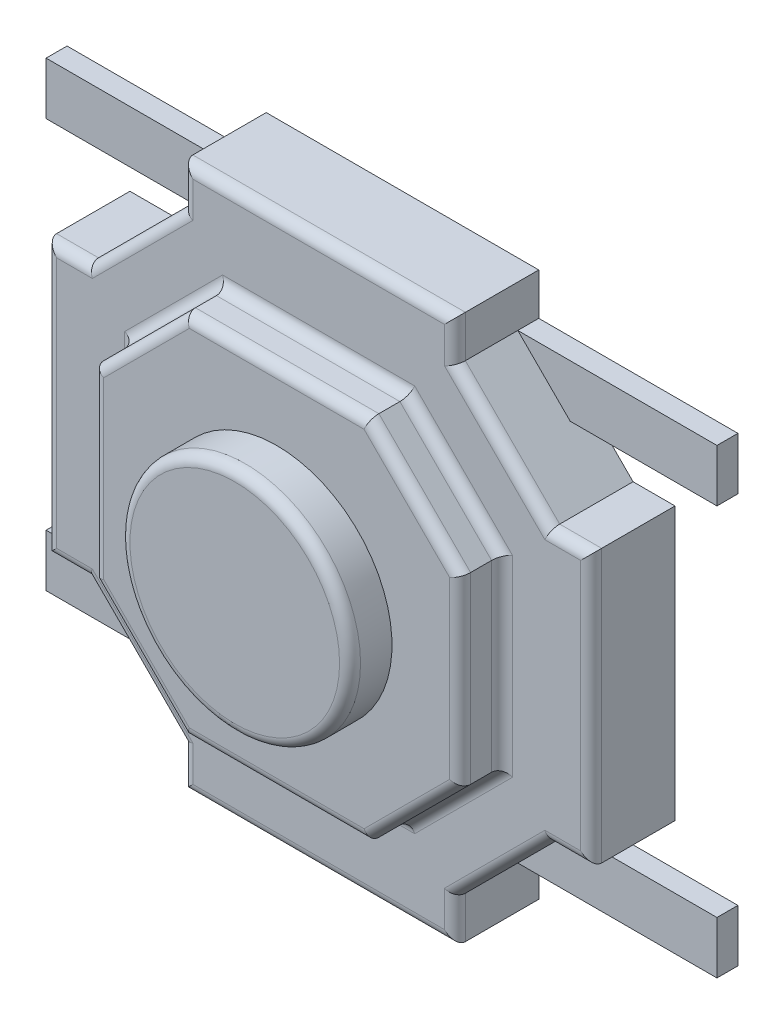
SolidWorks part; units mm, degrees
ref_plane "Plan de face" through (0, 0, 0) normal (0, 0, 1) x (1, 0, 0)
ref_plane "Plan de dessus" through (0, 0, 0) normal (0, 1, 0) x (1, 0, 0)
ref_plane "Plan de droite" through (0, 0, 0) normal (1, 0, 0) x (0, 0, -1)
sketch "Sketch1" plane through (0, 0, 0) normal (0, 0, 1) x (1, 0, 0)
  line L0 (0, 2.6) -> (0, -2.6) construction
  line L1 (-1.3, 2.6) -> (1.3, 2.6)
  line L2 (-2.6, 1.3) -> (-2.6, -1.3)
  line L3 (-1.3, -2.6) -> (1.3, -2.6)
  line L4 (2.6, 1.3) -> (2.6, -1.3)
  line L5 (-2.6, 2.6) -> (2.6, -2.6) construction
  line L6 (-3.9775, -1.9888) -> (2.6, 1.3) construction
  line L7 (-2.6, 0) -> (2.6, 0) construction
  line L8 (-1.3, 2.6) -> (-1.3, -2.6) construction
  line L9 (1.3, 2.6) -> (1.3, -2.6) construction
  line L10 (-2.6, 1.3) -> (2.6, 1.3) construction
  line L11 (-2.6, -1.3) -> (2.6, -1.3) construction
  line L12 (-1.3, -2.6) -> (-1.3, -2.2)
  line L13 (-1.3, -2.2) -> (-2.2, -1.3)
  line L14 (-2.2, -1.3) -> (-2.6, -1.3)
  line L15 (1.3, -2.6) -> (1.3, -2.2)
  line L16 (1.3, -2.2) -> (2.2, -1.3)
  line L17 (2.2, -1.3) -> (2.6, -1.3)
  line L18 (-1.3, 2.2) -> (-2.2, 1.3)
  line L19 (-1.3, 2.6) -> (-1.3, 2.2)
  line L20 (2.2, 1.3) -> (2.6, 1.3)
  line L21 (1.3, 2.6) -> (1.3, 2.2)
  line L22 (1.3, 2.2) -> (2.2, 1.3)
  line L23 (-2.6, 1.3) -> (-2.2, 1.3)
  line L24 (-1.75, 1.75) -> (1.75, 1.75) construction
  line L25 (1.75, 1.75) -> (-1.75, -1.75) construction
  line L26 (-1.75, -1.75) -> (1.75, -1.75) construction
  point P0 (0, 0)
  dimension "D3" = 1.3
  dimension "D6" = 1.3
  dimension "D7" = 0.4
  dimension "D8" = 0.4
extrude "Boss-Extrude1" add sketch "Sketch1" along normal blind 0.8
sketch "Sketch3" plane through (0, 0, 0) normal (0, 0, 1) x (1, 0, 0)
  line L4 (1.3, -2.2) -> (2.2, -1.3) construction
  line L5 (1.75, -1.75) -> (-1.75, -1.75) construction
  line L6 (-2.2, -1.3) -> (-1.3, -2.2) construction
  line L8 (-2.2861, 0) -> (3.4784, 0) construction
  line L9 (-3.2, 2.2) -> (3.2, 2.2)
  line L10 (-3.2, 2.2) -> (-3.2, 1.7)
  line L11 (-3.2, 1.7) -> (3.2, 1.7)
  line L12 (3.2, 2.2) -> (3.2, 1.7)
  line L13 (-3.2, 2.2) -> (3.2, 1.7) construction
  line L14 (-3.2, 1.7) -> (3.2, 2.2) construction
  line L15 (-3.2, -1.7) -> (3.2, -2.2) construction
  line L16 (-3.2, -2.2) -> (3.2, -1.7) construction
  line L17 (-1.75, -1.75) -> (1.75, -1.75) construction
  line L18 (3.2, -2.2) -> (3.2, -1.7)
  line L19 (-3.2, -1.7) -> (3.2, -1.7)
  line L20 (-3.2, -2.2) -> (-3.2, -1.7)
  line L21 (-3.2, -2.2) -> (3.2, -2.2)
  point P6 (0, 1.95)
  point P24 (0, -1.95)
  dimension "D1" = 0.5
  dimension "D2" = 6.4
  dimension "D3" = 1.7
extrude "Boss-Extrude2" add sketch "Sketch3" along normal blind 0.2
sketch "Sketch4" plane through (0, 0, 0.8) normal (0, 0, 1) x (1, 0, 0)
  line L0 (1.8, -1.7) -> (1.3, -2.2) construction
  line L1 (-0.875, 1.75) -> (0.875, 1.75)
  line L2 (-1.75, 0.875) -> (-1.75, -0.875)
  line L3 (-0.875, -1.75) -> (0.875, -1.75)
  line L4 (1.75, 0.875) -> (1.75, -0.875)
  line L5 (-1.53, 1.9249) -> (1.55, -1.95) construction
  line L6 (-2.6772, -1.3386) -> (1.75, 0.875) construction
  line L7 (-1.75, 0) -> (1.75, 0) construction
  line L8 (0, 1.75) -> (0, -1.75) construction
  line L9 (0, -0.8397) -> (-1.75, -0.8397) construction
  line L10 (-0.875, -0.8397) -> (-0.875, 1.75) construction
  line L11 (0.6609, 1.75) -> (0.6609, 0) construction
  line L12 (0.6609, 0.875) -> (-1.75, 0.875) construction
  line L13 (-1.75, 0.875) -> (-0.875, 1.75)
  line L14 (1.75, 0.875) -> (0.875, 1.75)
  line L15 (1.75, -0.875) -> (0.875, -1.75)
  line L16 (-1.75, -0.875) -> (-0.875, -1.75)
  point P0 (0, 0)
extrude "Boss-Extrude3" add sketch "Sketch4" along normal blind 0.4
sketch "Sketch5" plane through (0, 0, 1.2) normal (0, 0, 1) x (1, 0, 0)
  circle A0 centre (0, 0) radius 1.1
extrude "Boss-Extrude4" add sketch "Sketch5" along normal blind 0.4
fillet "Fillet2" radius 0.1 1 edges at (1.1, 0, 1.6)
fillet "Fillet3" radius 0.1 24 edges at (0, 1.75, 0.8) (-1.3125, 1.3125, 0.8) (-1.75, 0, 0.8) (-1.3125, -1.3125, 0.8) (0, -1.75, 0.8) (1.3125, -1.3125, 0.8) (1.75, 0, 0.8) (1.3125, 1.3125, 0.8) (2.6, 0, 0.8) (2.4, -1.3, 0.8) (1.75, -1.75, 0.8) (1.3, -2.4, 0.8) (0, -2.6, 0.8) (-1.3, -2.4, 0.8) (-1.75, -1.75, 0.8) (-2.4, -1.3, 0.8) (-2.6, 0, 0.8) (-2.4, 1.3, 0.8) (-1.75, 1.75, 0.8) (-1.3, 2.4, 0.8) (0, 2.6, 0.8) (1.3, 2.4, 0.8) (1.75, 1.75, 0.8) (2.4, 1.3, 0.8)
fillet "Fillet4" radius 0.1 8 edges at (1.3125, 1.3125, 1.2) (0, 1.75, 1.2) (1.75, 0, 1.2) (1.3125, -1.3125, 1.2) (0, -1.75, 1.2) (-1.3125, -1.3125, 1.2) (-1.75, 0, 1.2) (-1.3125, 1.3125, 1.2)
